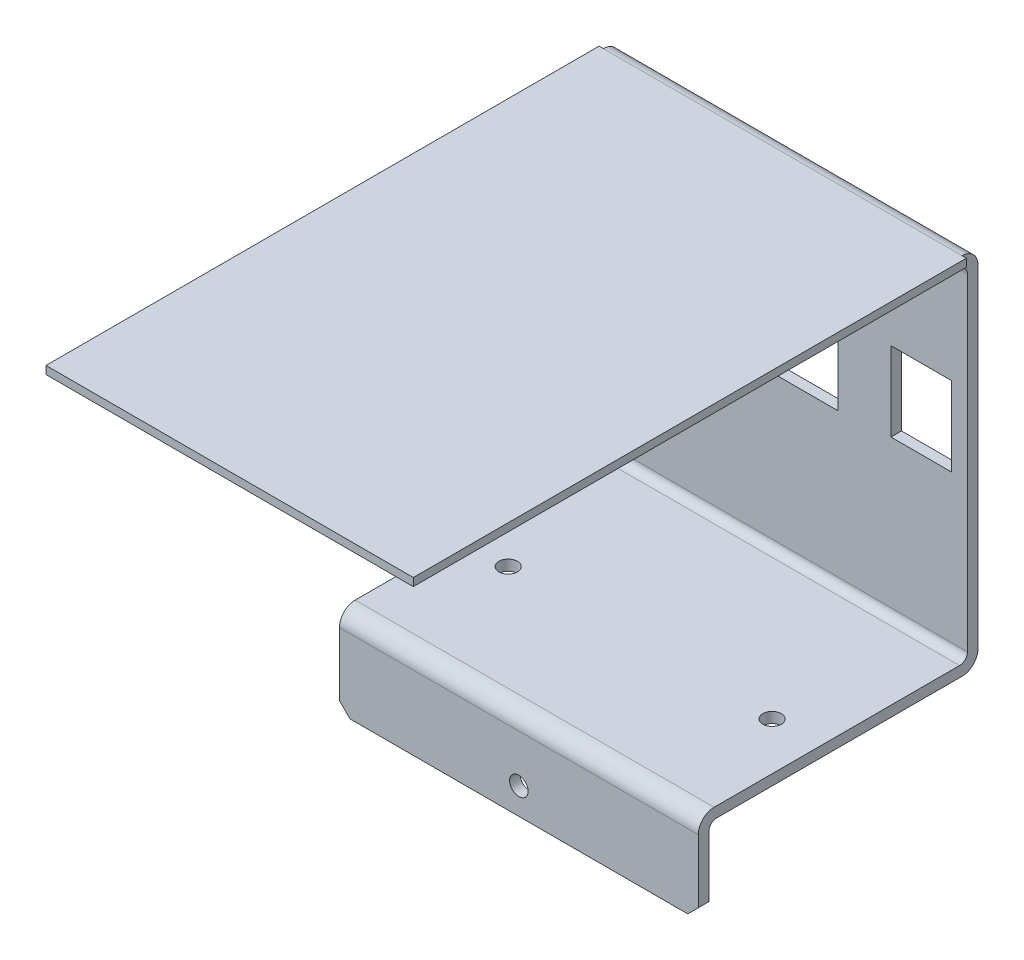
SolidWorks part; units mm, degrees
ref_plane "Front Plane" through (0, 0, 0) normal (0, 0, 1) x (1, 0, 0)
ref_plane "Top Plane" through (0, 0, 0) normal (0, 1, 0) x (1, 0, 0)
ref_plane "Right Plane" through (0, 0, 0) normal (1, 0, 0) x (0, 0, -1)
sketch "Sketch1" plane through (0, 0, 0) normal (0, 1, 0) x (1, 0, 0)
  line L1 (-34, -53.5) -> (34, -53.5)
  line L2 (-34, -53.5) -> (-34, 53.5)
  line L3 (-34, 53.5) -> (34, 53.5)
  line L4 (34, -53.5) -> (34, 53.5)
  line L5 (-34, -53.5) -> (34, 53.5) construction
  line L6 (-34, 53.5) -> (34, -53.5) construction
  point P0 (0, 0)
  dimension "D1" = 68
  dimension "D2" = 107
extrude "Boss-Extrude1" add sketch "Sketch1" along normal blind 2
sketch "Sketch2" plane through (0, 0, 0) normal (0, -1, 0) x (1, 0, 0)
  line L0 (34, 53.5) -> (34, -53.5) construction
  line L1 (-34, -53.5) -> (34, -53.5)
  line L2 (-34, -53.5) -> (-34, -51.5)
  line L3 (-34, -51.5) -> (34, -51.5)
  line L4 (34, -53.5) -> (34, -51.5)
  dimension "D1" = 2
extrude "Boss-Extrude2" add sketch "Sketch2" along normal blind 67
sketch "Sketch4" plane through (0, 0, -53.5) normal (0, 0, -1) x (-1, 0, 0)
  line L0 (-34, 2) -> (34, 2) construction
  line L1 (-31, -20.5) -> (-19.5, -20.5)
  line L2 (-31, -20.5) -> (-31, -35.5)
  line L3 (-31, -35.5) -> (-19.5, -35.5)
  line L4 (-19.5, -20.5) -> (-19.5, -35.5)
  line L5 (-9.4531, -15.2) -> (28.5469, -15.2)
  line L6 (-9.4531, -15.2) -> (-9.4531, -36.2)
  line L7 (-9.4531, -36.2) -> (28.5469, -36.2)
  line L8 (28.5469, -15.2) -> (28.5469, -36.2)
  line L9 (-34, 2) -> (-34, -67) construction
  dimension "D1" = 11.5
  dimension "D2" = 15
  dimension "D3" = 38
  dimension "D4" = 21
  dimension "D5" = 17.2
  dimension "D6" = 22.5
  dimension "D7" = 3
extrude "Cut-Extrude2" cut sketch "Sketch4" against normal up to next
sketch "Sketch5" plane through (0, 0, -51.5) normal (0, 0, 1) x (1, 0, 0)
  line L0 (34, -67) -> (34, 0) construction
  line L1 (-34, -67) -> (34, -67)
  line L2 (-34, -67) -> (-34, -65)
  line L3 (-34, -65) -> (34, -65)
  line L4 (34, -67) -> (34, -65)
  line L5 (-34, -67) -> (-34, 0) construction
  dimension "D1" = 2
extrude "Boss-Extrude3" add sketch "Sketch5" along normal blind 51
sketch "Sketch6" plane through (0, -67, 0) normal (0, -1, 0) x (1, 0, 0)
  line L0 (34, -53.5) -> (34, -0.5) construction
  line L1 (-34, -0.5) -> (34, -0.5)
  line L2 (-34, -0.5) -> (-34, -2.5)
  line L3 (-34, -2.5) -> (34, -2.5)
  line L4 (34, -0.5) -> (34, -2.5)
  line L5 (-34, -0.5) -> (-34, -53.5) construction
  dimension "D1" = 2
extrude "Boss-Extrude4" add sketch "Sketch6" along normal blind 15
sketch "Sketch8" plane through (0, 2, 0) normal (0, 1, 0) x (1, 0, 0)
  line L6 (34, 53.5) -> (-34, 53.5) construction
  line L7 (-34.8, 50.5) -> (-34, 50.5)
  line L8 (-34, 53.5) -> (-34, -53.5) construction
  line L9 (34.8, -54.3) -> (34.8, 53.5)
  line L10 (-34.8, -54.3) -> (34.8, -54.3)
  line L11 (-34.8, 53.5) -> (-34.8, -54.3)
  line L12 (34.8, -54.3) -> (34.8, 50.5)
  line L13 (-34.8, -54.3) -> (34.8, -54.3)
  line L14 (-34.8, 50.5) -> (-34.8, -54.3)
  line L15 (34, 50.5) -> (34.8, 50.5)
  line L16 (34, -53.5) -> (34, 53.5) construction
  line L21 (34, -53.5) -> (34, 53.5)
  line L22 (34, 53.5) -> (-34, 53.5)
  line L23 (-34, 53.5) -> (-34, -53.5)
  line L24 (-34, -53.5) -> (34, -53.5)
  line L25 (34, -53.5) -> (34, 50.5)
  line L27 (-34, 50.5) -> (-34, -53.5)
  line L28 (-34, -53.5) -> (34, -53.5)
  dimension "D2" = 3
  dimension "D3" = 3
  dimension "D1" = 0.8
  dimension "D4" = 0
extrude "Boss-Extrude5" add sketch "Sketch8" against normal blind 1.5
sketch "Sketch9" plane through (0, -67, 0) normal (0, -1, 0) x (1, 0, 0)
  line L0 (-34, -2.5) -> (-34, -53.5) construction
  line L1 (34, -53.5) -> (34, -2.5) construction
  line L2 (-34, -2.5) -> (34, -2.5) construction
  circle A0 centre (-25, -23.48) radius 1.75
  circle A1 centre (25, -23.48) radius 1.75
  dimension "D1" = 3.5
  dimension "D2" = 9
  dimension "D3" = 9
  dimension "D5" = 3.5
  dimension "D4" = 20.98
extrude "Cut-Extrude4" cut sketch "Sketch9" against normal up to next
fillet "Fillet1" radius 1.5 1 edges
fillet "Fillet2" radius 3 1 edges at (0, -65, -0.5)
fillet "Fillet3" radius 1.5 1 edges at (0, -65, -51.5)
fillet "Fillet4" radius 3 1 edges at (0, -67, -53.5)
fillet "Fillet5" radius 1.5 1 edges
fillet "Fillet6" radius 3 1 edges at (0, 2, -53.5)
sketch "Sketch10" plane through (0, 0, -0.5) normal (0, 0, 1) x (1, 0, 0)
  line L0 (34, -82) -> (-34, -82) construction
  circle A0 centre (0, -77) radius 1.75
  dimension "D1" = 5
  dimension "D2" = 3.5
extrude "Cut-Extrude5" cut sketch "Sketch10" against normal up to next
chamfer "Chamfer1" distance 2 angle 45 2 edges at (-34, -82, -1.5) (34, -82, -1.5)
